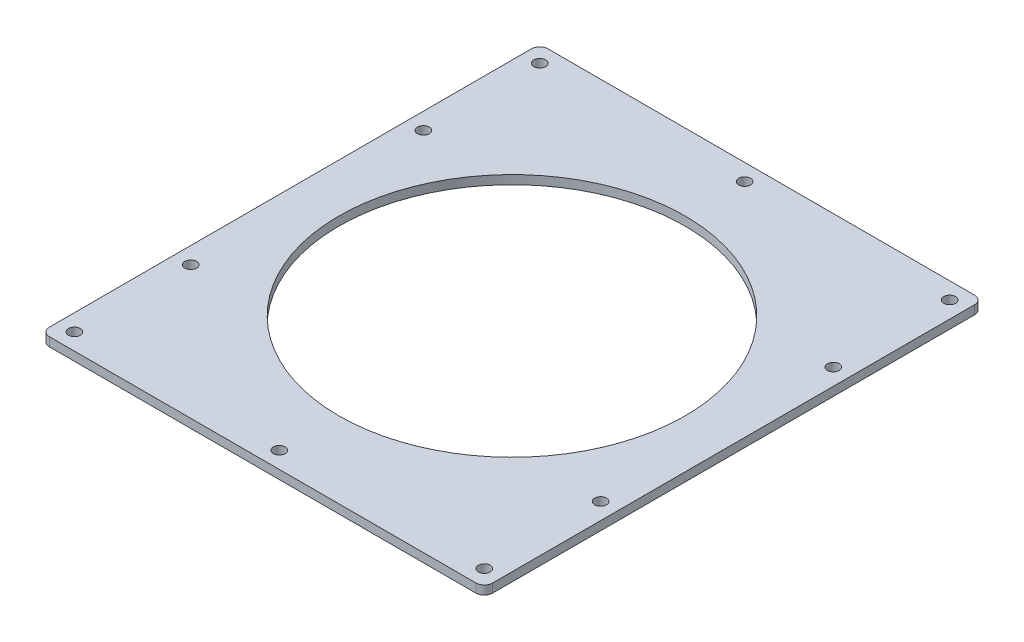
SolidWorks part; units mm, degrees
ref_plane "Front Plane" through (0, 0, 0) normal (0, 0, 1) x (1, 0, 0)
ref_plane "Top Plane" through (0, 0, 0) normal (0, 1, 0) x (1, 0, 0)
ref_plane "Right Plane" through (0, 0, 0) normal (1, 0, 0) x (0, 0, -1)
sketch "Sketch1" plane through (0, 0, 0) normal (0, 1, 0) x (1, 0, 0)
  line L0 (-80, 0) -> (80, 0) construction
  line L1 (-80, -90) -> (80, -90)
  line L2 (-80, -90) -> (-80, 90)
  line L3 (-80, 90) -> (80, 90)
  line L4 (80, -90) -> (80, 90)
  line L5 (-80, -90) -> (80, 90) construction
  line L6 (-80, 90) -> (80, -90) construction
  line L7 (0, 90) -> (0, -90) construction
  circle A0 centre (0, 0) radius 62.5
  circle A4 centre (-74, -84) radius 2.125
  circle A5 centre (-74, -42) radius 2.125
  circle A6 centre (-74, 84) radius 2.125
  circle A7 centre (74, -84) radius 2.125
  circle A8 centre (74, -42) radius 2.125
  circle A9 centre (74, 84) radius 2.125
  circle A10 centre (0, -84) radius 2.125
  circle A11 centre (0, 84) radius 2.125
  circle A13 centre (74, 42) radius 2.125
  circle A14 centre (-74, 42) radius 2.125
  point P0 (0, 0)
  point P16 (0, 0)
  dimension "D1" = 125
  dimension "D7" = 4.25
  dimension "D10" = 4.25
  dimension "D11" = 4.25
  dimension "D5" = 180
  dimension "D6" = 160
  dimension "D8" = 6
  dimension "D9" = 6
  dimension "D12" = 6
  dimension "D14" = 6
  dimension "42" = 42
extrude "Boss-Extrude1" add sketch "Sketch1" along normal blind 3.175
fillet "Fillet1" radius 3 4 edges at (-80, 1.5875, -90) (80, 1.5875, 90) (80, 1.5875, -90) (-80, 1.5875, 90)
